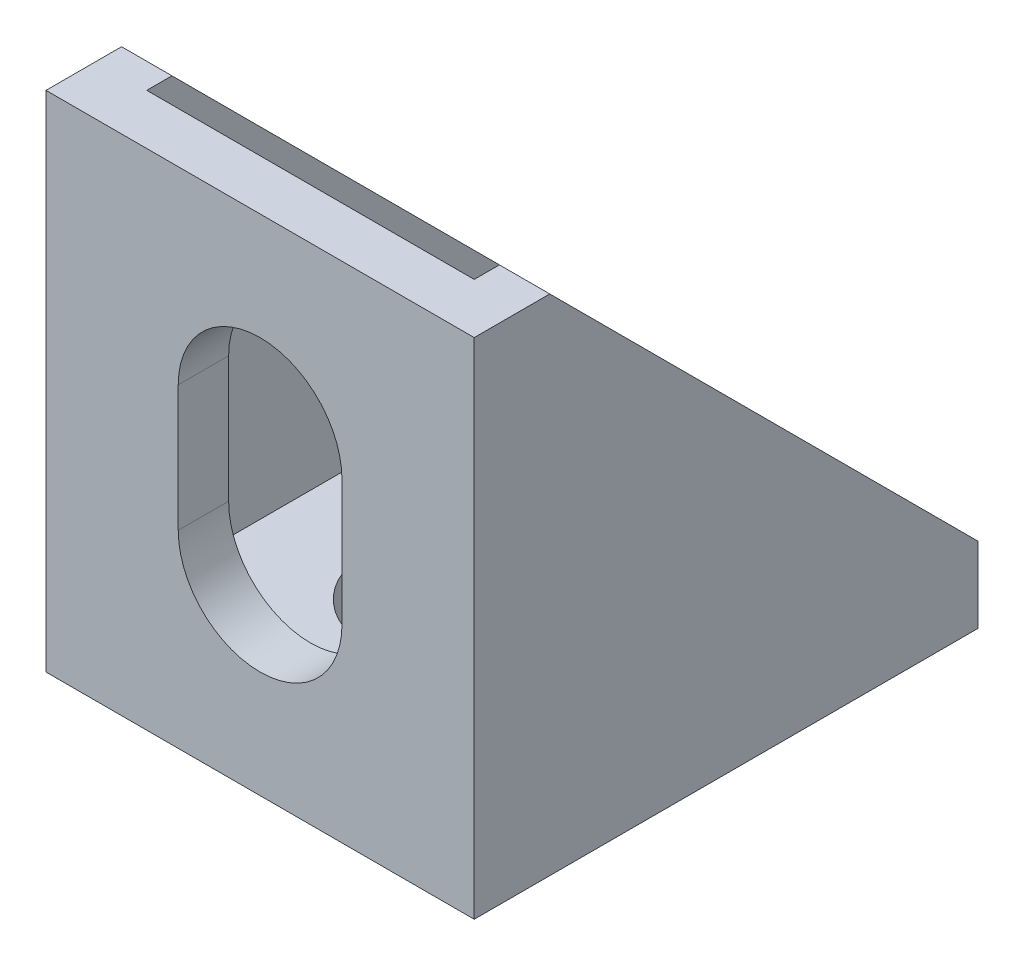
SolidWorks part; units mm, degrees
ref_plane "Front Plane" through (0, 0, 0) normal (0, 0, 1) x (1, 0, 0)
ref_plane "Top Plane" through (0, 0, 0) normal (0, 1, 0) x (1, 0, 0)
ref_plane "Right Plane" through (0, 0, 0) normal (1, 0, 0) x (0, 0, -1)
sketch "Sketch1" plane through (0, 0, 0) normal (1, 0, 0) x (0, 0, -1)
  line L0 (3, 20) -> (0, 20)
  line L1 (0, 20) -> (0, 0)
  line L2 (0, 0) -> (20, 0)
  line L3 (20, 0) -> (20, 3)
  line L4 (20, 3) -> (3, 20)
  dimension "D1" = 3
  dimension "D2" = 20
extrude "Body" add sketch "Sketch1" along normal mid plane 17
sketch "Sketch2" plane through (0, 0, -20) normal (0, 0, -1) x (-1, 0, 0)
  line L0 (-8.5, 3) -> (8.5, 3) construction
  line L1 (-6.5, 3) -> (6.5, 3)
  line L2 (-6.5, 3) -> (-6.5, 20)
  line L3 (-6.5, 20) -> (6.5, 20)
  line L4 (6.5, 3) -> (6.5, 20)
  line L5 (-8.5, 20) -> (8.5, 20) construction
  line L6 (8.5, 3) -> (8.5, 20) construction
  dimension "D1" = 2
  dimension "D2" = 2
extrude "Extusion" cut sketch "Sketch2" against normal offset from surface (18 mm away) 2 up to face at (0, 10, 0)
sketch "Sketch3" plane through (0, 0, -2) normal (0, 0, -1) x (-1, 0, 0)
  line L0 (0, 7.5) -> (0, 12.5) construction
  line L1 (-3.25, 7.5) -> (-3.25, 12.5)
  line L2 (3.25, 7.5) -> (3.25, 12.5)
  line L3 (-6.5, 20) -> (6.5, 20) construction
  arc A0 (-3.25, 7.5) -> (3.25, 7.5) centre (0, 7.5) ccw
  arc A1 (3.25, 12.5) -> (-3.25, 12.5) centre (0, 12.5) ccw
  point P2 (0, 10)
  dimension "D1" = 6.5
  dimension "D2" = 5
  dimension "D3" = 10
extrude "Hole_A" cut sketch "Sketch3" against normal through all
sketch "Sketch4" plane through (0, 3, 0) normal (0, 1, 0) x (1, 0, 0)
  line L0 (0, 7.5) -> (0, 12.5) construction
  line L1 (-3.25, 7.5) -> (-3.25, 12.5)
  line L2 (3.25, 7.5) -> (3.25, 12.5)
  line L4 (6.5, 20) -> (-6.5, 20) construction
  arc A0 (-3.25, 7.5) -> (3.25, 7.5) centre (0, 7.5) ccw
  arc A1 (3.25, 12.5) -> (-3.25, 12.5) centre (0, 12.5) ccw
  point P3 (0, 10)
  dimension "D1" = 6.5
  dimension "D2" = 5
  dimension "D3" = 10
extrude "Hole_B" cut sketch "Sketch4" against normal blind 17
